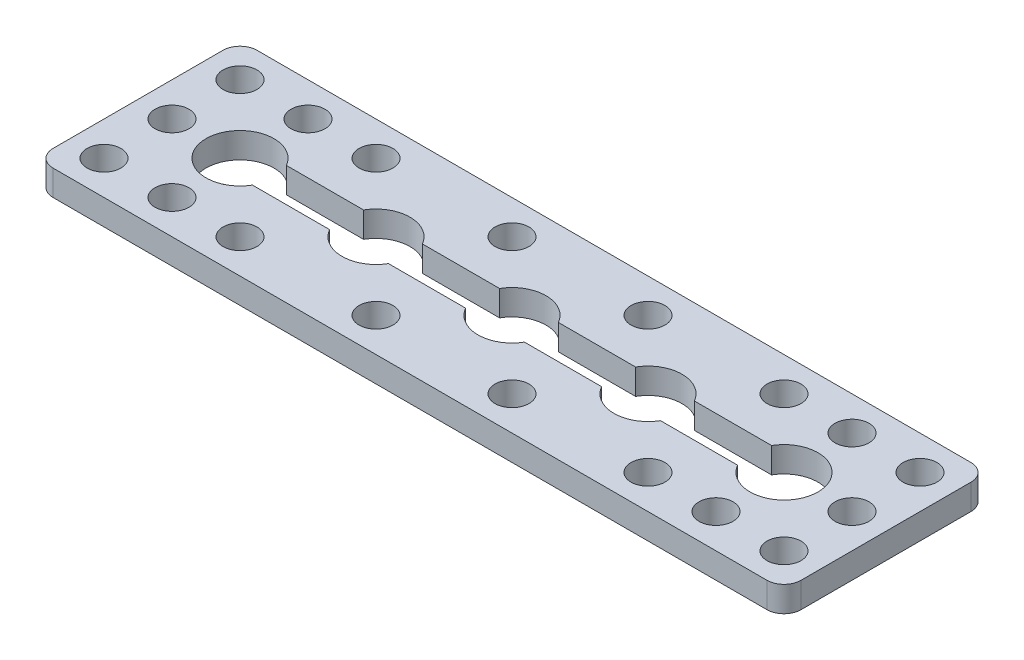
SolidWorks part; units mm, degrees
material "6061 Alloy"
ref_plane "前视基准面" through (0, 0, 0) normal (0, 0, 1) x (1, 0, 0)
ref_plane "上视基准面" through (0, 0, 0) normal (0, 1, 0) x (1, 0, 0)
ref_plane "右视基准面" through (0, 0, 0) normal (1, 0, 0) x (0, 0, -1)
other "Configuration Table"
sketch "Sketch1" plane through (0, 0, 0) normal (0, 1, 0) x (1, 0, 0)
  line L0 (-32.4805, -0.5685) -> (55.5195, -0.5685)
  line L1 (-30.4805, 11.4315) -> (53.5195, 11.4315)
  line L2 (-32.4805, 9.4315) -> (-32.4805, -10.5685)
  line L3 (-30.4805, -12.5685) -> (53.5195, -12.5685)
  line L4 (55.5195, 9.4315) -> (55.5195, -10.5685)
  line L5 (11.5195, 11.4315) -> (11.5195, -12.5685)
  line L7 (43.5195, -2.5685) -> (-20.4805, -2.5685)
  line L8 (43.5195, -2.5685) -> (43.5195, 1.4315)
  line L9 (43.5195, 1.4315) -> (-20.4805, 1.4315)
  line L10 (-20.4805, -2.5685) -> (-20.4805, 1.4315)
  line L11 (43.5195, -2.5685) -> (-20.4805, 1.4315) construction
  line L12 (43.5195, 1.4315) -> (-20.4805, -2.5685) construction
  arc A0 (53.5195, -12.5685) -> (55.5195, -10.5685) centre (53.5195, -10.5685) ccw
  arc A1 (53.5195, 11.4315) -> (55.5195, 9.4315) centre (53.5195, 9.4315) cw
  arc A2 (-32.4805, -10.5685) -> (-30.4805, -12.5685) centre (-30.4805, -10.5685) ccw
  arc A3 (-30.4805, 11.4315) -> (-32.4805, 9.4315) centre (-30.4805, 9.4315) ccw
  circle A4 centre (-28.4805, 7.4315) radius 2
  circle A5 centre (-20.4805, 7.4315) radius 2
  circle A6 centre (-12.4805, 7.4315) radius 2
  circle A7 centre (3.5195, 7.4315) radius 2
  circle A8 centre (-28.4805, -0.5685) radius 2
  circle A9 centre (-20.4805, -0.5685) radius 4
  circle A10 centre (-4.4805, -0.5685) radius 4
  circle A11 centre (11.5195, -0.5685) radius 4
  circle A12 centre (3.5195, -8.5685) radius 2
  circle A13 centre (-12.4805, -8.5685) radius 2
  circle A14 centre (-20.4805, -8.5685) radius 2
  circle A15 centre (-28.4805, -8.5685) radius 2
  circle A16 centre (19.5195, -8.5685) radius 2
  circle A17 centre (35.5195, -8.5685) radius 2
  circle A18 centre (43.5195, -8.5685) radius 2
  circle A19 centre (51.5195, -8.5685) radius 2
  circle A20 centre (51.5195, -0.5685) radius 2
  circle A21 centre (27.5195, -0.5685) radius 4
  circle A22 centre (43.5195, -0.5685) radius 4
  circle A23 centre (35.5195, 7.4315) radius 2
  circle A24 centre (19.5195, 7.4315) radius 2
  circle A25 centre (43.5195, 7.4315) radius 2
  circle A26 centre (51.5195, 7.4315) radius 2
  point P10 (55.5195, 11.4315)
  point P13 (-32.4805, -12.5685)
  point P16 (-32.4805, 11.4315)
  point P29 (11.5195, -0.5685)
  dimension "D3" = 2
  dimension "D4" = 4
  dimension "D6" = 8
  dimension "D8" = 16
  dimension "D9" = 16
  dimension "D10" = 16
  dimension "D1" = 24
  dimension "D2" = 88
  dimension "D5" = 4
  dimension "D7" = 8
  dimension "4" = 4
extrude "Boss-Extrude1" add sketch "Sketch1" along normal blind 3 contours A11 L7 A10 A9 L0 A8 L2 A2 L3 L5 A14 A12 A13 A15 | A11 L5 L1 A3 L2 L0 A8 A9 L9 A10 A7 A6 A5 A4 | L9 A22 L0 A20 L4 A1 L1 L5 A11 A21 A25 A23 A24 A26 | L0 A22 L7 A21 A11 L5 L3 A0 L4 A20 A19 A18 A17 A16
